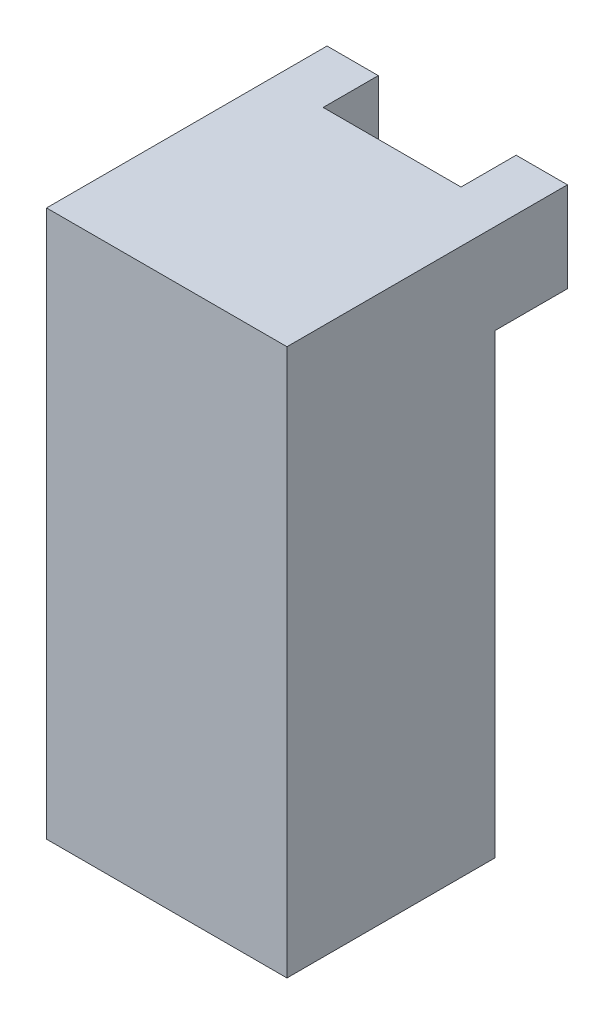
SolidWorks part; units mm, degrees
ref_plane "Front Plane" through (0, 0, 0) normal (0, 0, 1) x (1, 0, 0)
ref_plane "Top Plane" through (0, 0, 0) normal (0, 1, 0) x (1, 0, 0)
ref_plane "Right Plane" through (0, 0, 0) normal (1, 0, 0) x (0, 0, -1)
sketch "Sketch1" plane through (0, 0, 0) normal (0, 1, 0) x (1, 0, 0)
  line L1 (-2.79, -2.415) -> (2.79, -2.415)
  line L2 (-2.79, -2.415) -> (-2.79, 2.415)
  line L3 (-2.79, 2.415) -> (2.79, 2.415)
  line L4 (2.79, -2.415) -> (2.79, 2.415)
  line L5 (-2.79, -2.415) -> (2.79, 2.415) construction
  line L6 (-2.79, 2.415) -> (2.79, -2.415) construction
  point P0 (0, 0)
  dimension "D1" = 5.58
  dimension "D2" = 4.83
extrude "Boss-Extrude1" add sketch "Sketch1" along normal mid plane 12.69
sketch "Sketch2" plane through (0, 6.345, 0) normal (0, 1, 0) x (1, 0, 0)
  line L0 (-2.79, -2.415) -> (2.79, -2.415) construction
  line L1 (-2.79, 2.415) -> (-1.6, 2.415)
  line L2 (-2.79, 2.415) -> (-2.79, 4.095)
  line L3 (-2.79, 4.095) -> (-1.6, 4.095)
  line L4 (-1.6, 2.415) -> (-1.6, 4.095)
  line L5 (2.79, 2.415) -> (1.6, 2.415)
  line L6 (2.79, 2.415) -> (2.79, 4.095)
  line L7 (2.79, 4.095) -> (1.6, 4.095)
  line L8 (1.6, 2.415) -> (1.6, 4.095)
  dimension "D1" = 6.51
  dimension "D2" = 3.2
extrude "Boss-Extrude2" add sketch "Sketch2" against normal blind 2.09
sketch "Sketch4" plane through (0, 6.345, 0) normal (0, 1, 0) x (1, 0, 0)
  line L0 (-1.6, 2.415) -> (-1.6, 4.095) construction
  line L1 (-1.6, 2.815) -> (1.6, 2.815)
  line L2 (-1.6, 2.815) -> (-1.6, 2.415)
  line L3 (-1.6, 2.415) -> (1.6, 2.415)
  line L4 (1.6, 2.815) -> (1.6, 2.415)
  dimension "D1" = 0.4
extrude "Boss-Extrude3" add sketch "Sketch4" against normal up to surface (2.09 mm away)
